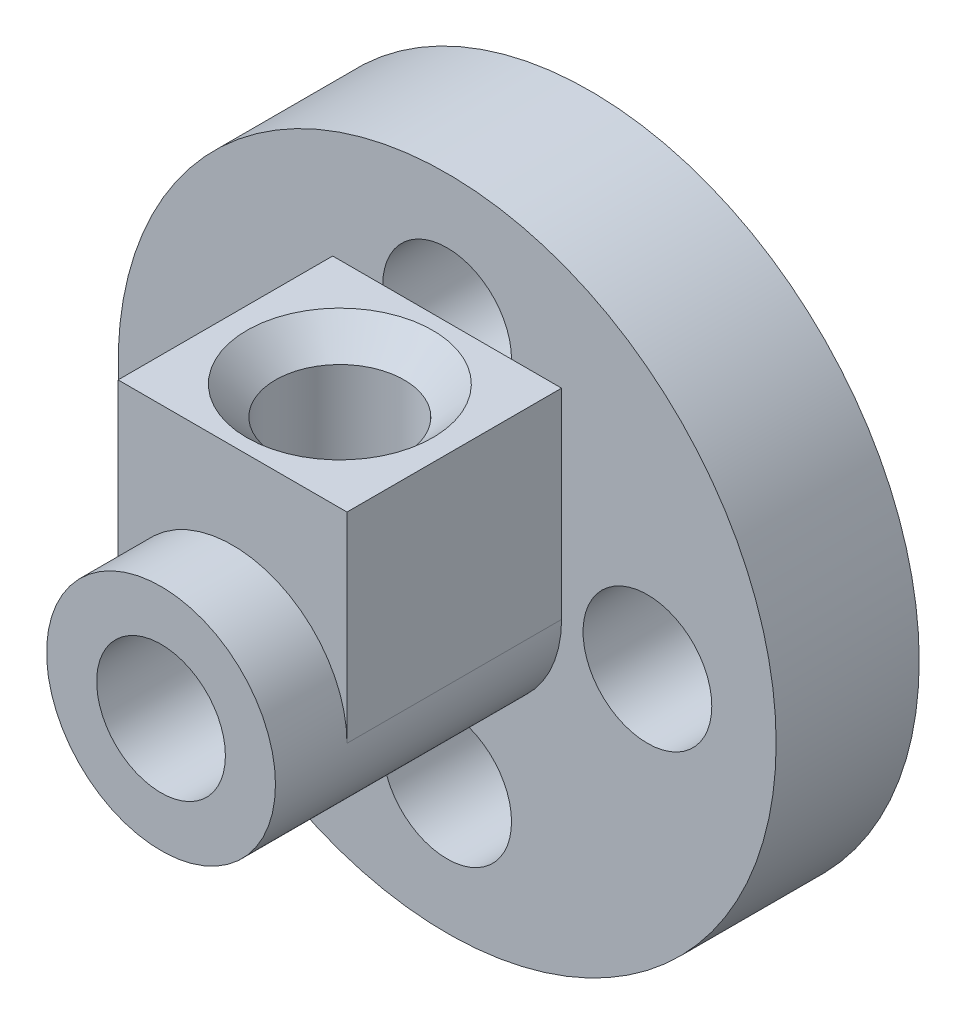
SolidWorks part; units mm, degrees
ref_plane "Front Plane" through (0, 0, 0) normal (0, 0, 1) x (1, 0, 0)
ref_plane "Top Plane" through (0, 0, 0) normal (0, 1, 0) x (1, 0, 0)
ref_plane "Right Plane" through (0, 0, 0) normal (1, 0, 0) x (0, 0, -1)
sketch "Sketch1" plane through (0, 0, 0) normal (0, 0, 1) x (1, 0, 0)
  circle A0 centre (0, 0) radius 11.5
  dimension "D1" = 23
extrude "Boss-Extrude1" add sketch "Sketch1" along normal blind 5
sketch "Sketch2" plane through (0, 0, 5) normal (0, 0, 1) x (1, 0, 0)
  line L0 (0, 0) -> (0, 7) construction
  circle A0 centre (0, 7) radius 2.25
  dimension "D2" = 4.5
  dimension "D1" = 7
extrude "Cut-Extrude1" cut sketch "Sketch2" against normal through all
pattern_circular "CirPattern1" count 4 over 360 about axis through (0, 0, 0) along (0, 0, 1) of "Cut-Extrude1"
sketch "Sketch3" plane through (0, 0, 5) normal (0, 0, 1) x (1, 0, 0)
  circle A0 centre (0, 0) radius 4
  dimension "D1" = 8
extrude "Boss-Extrude2" add sketch "Sketch3" along normal blind 10
sketch "Sketch4" plane through (0, 0, 15) normal (0, 0, 1) x (1, 0, 0)
  circle A0 centre (0, 0) radius 2.25
  dimension "D1" = 4.5
extrude "Cut-Extrude2" cut sketch "Sketch4" against normal through all
ref_plane "Plane1" through (0, 7, 0) normal (0, 1, 0) x (1, 0, 0)
sketch "Sketch5" plane through (0, 7, 0) normal (0, 1, 0) x (1, 0, 0)
  line L0 (-4, -5) -> (-4, -15) construction
  line L1 (-4, -5) -> (4, -5)
  line L2 (-4, -5) -> (-4, -12.5)
  line L3 (-4, -12.5) -> (4, -12.5)
  line L4 (4, -5) -> (4, -12.5)
  line L5 (4, -15) -> (4, -5) construction
  line L6 (-4, -15) -> (4, -15) construction
  dimension "D1" = 7.5
  dimension "D2" = 2.5
extrude "Boss-Extrude3" add sketch "Sketch5" against normal up to next
sketch "Sketch6" plane through (0, 7, 0) normal (0, 1, 0) x (1, 0, 0)
  line L0 (-4, -8.75) -> (4, -8.75) construction
  line L1 (-4, -5) -> (-4, -12.5) construction
  line L2 (4, -12.5) -> (4, -5) construction
  circle A0 centre (0, -8.75) radius 2.25
  dimension "D1" = 4.5
extrude "Cut-Extrude3" cut sketch "Sketch6" against normal blind 7
chamfer "Chamfer1" distance 1 angle 45 1 edges at (0, 7, 11)
chamfer "Chamfer2" distance 1 angle 45 4 edges at (-2.25, -7, 0) (-7, 2.25, 0) (7, -2.25, 0) (2.25, 7, 0)
